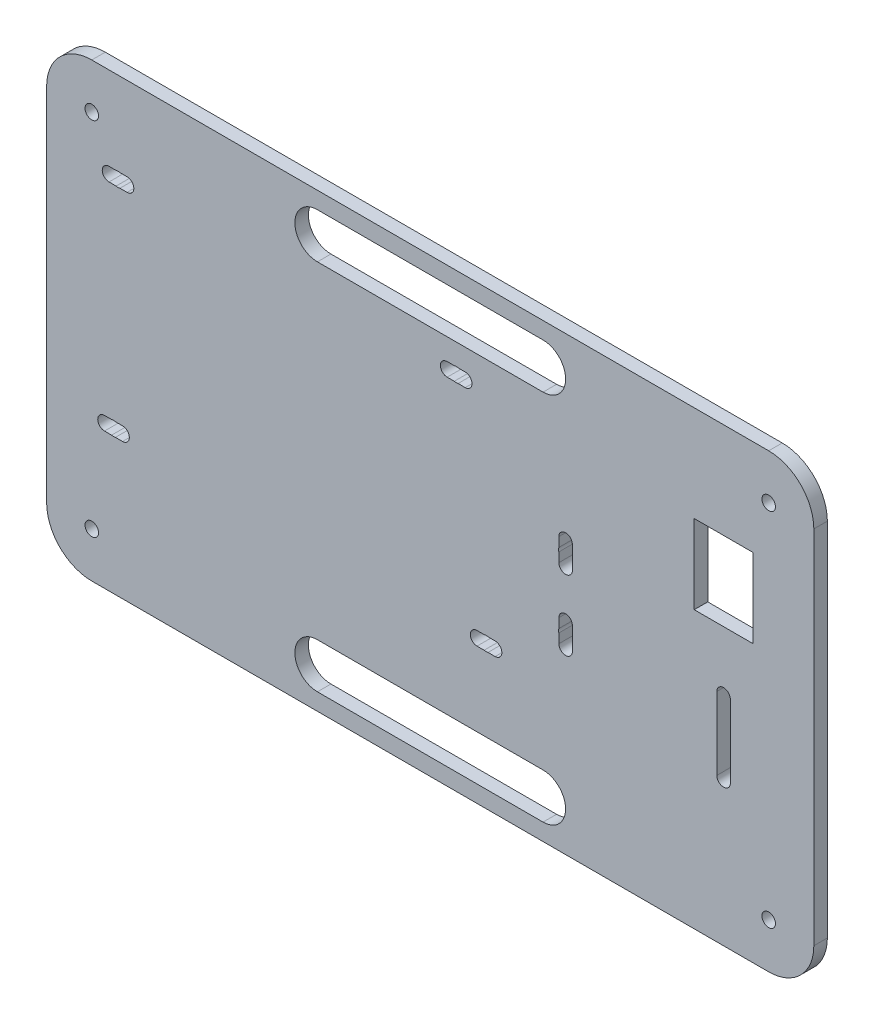
SolidWorks part; units mm, degrees
ref_plane "Front Plane" through (0, 0, 0) normal (0, 0, 1) x (1, 0, 0)
ref_plane "Top Plane" through (0, 0, 0) normal (0, 1, 0) x (1, 0, 0)
ref_plane "Right Plane" through (0, 0, 0) normal (1, 0, 0) x (0, 0, -1)
sketch "Sketch1" plane through (0, 0, 0) normal (0, 0, 1) x (1, 0, 0)
  line L0 (-85, 0) -> (85, 0) construction
  line L1 (-75, 50) -> (75, 50)
  line L2 (-85, 40) -> (-85, -40)
  line L3 (-75, -50) -> (75, -50)
  line L4 (85, 40) -> (85, -40)
  line L5 (-85, 50) -> (85, -50) construction
  line L6 (-85, -50) -> (85, 50) construction
  line L7 (0, 50) -> (0, -50) construction
  line L8 (-25, 41.2578) -> (25, 41.2578) construction
  line L9 (-25, 46.2578) -> (25, 46.2578)
  line L10 (-25, 36.2578) -> (25, 36.2578)
  line L11 (-25, -41.2578) -> (25, -41.2578) construction
  line L12 (-25, -46.2578) -> (25, -46.2578)
  line L13 (-25, -36.2578) -> (25, -36.2578)
  line L14 (30, 5.28) -> (30, 10.28) construction
  line L17 (28.5, 5.28) -> (28.5, 10.28)
  line L18 (31.5, 5.28) -> (31.5, 10.28)
  line L21 (30, -5.28) -> (30, -10.28) construction
  line L24 (28.5, -5.28) -> (28.5, -10.28)
  line L27 (31.5, -5.28) -> (31.5, -10.28)
  line L30 (-67.18, 30) -> (-71.18, 30) construction
  line L31 (-67.18, 28.5) -> (-71.18, 28.5)
  line L34 (-67.18, 31.5) -> (-71.18, 31.5)
  line L39 (65, -1.95) -> (65, -18.05) construction
  line L40 (58.5, 28.75) -> (71.5, 28.75)
  line L41 (58.5, 28.75) -> (58.5, 11.25)
  line L42 (58.5, 11.25) -> (71.5, 11.25)
  line L43 (71.5, 28.75) -> (71.5, 11.25)
  line L44 (58.5, 28.75) -> (71.5, 11.25) construction
  line L45 (58.5, 11.25) -> (71.5, 28.75) construction
  line L46 (66.5, -1.95) -> (66.5, -18.05)
  line L47 (63.5, -1.95) -> (63.5, -18.05)
  line L48 (3.75, 30) -> (7.75, 30) construction
  line L49 (3.75, 31.5) -> (7.75, 31.5)
  line L50 (3.75, 28.5) -> (7.75, 28.5)
  line L51 (10.37, -18.3) -> (14.37, -18.3) construction
  line L52 (10.37, -16.8) -> (14.37, -16.8)
  line L53 (10.37, -19.8) -> (14.37, -19.8)
  line L54 (-72.18, -18.3) -> (-68.18, -18.3) construction
  line L55 (-72.18, -16.8) -> (-68.18, -16.8)
  line L56 (-72.18, -19.8) -> (-68.18, -19.8)
  arc A0 (-25, 46.2578) -> (-25, 36.2578) centre (-25, 41.2578) ccw
  arc A1 (25, 36.2578) -> (25, 46.2578) centre (25, 41.2578) ccw
  arc A2 (-25, -46.2578) -> (-25, -36.2578) centre (-25, -41.2578) cw
  arc A3 (25, -36.2578) -> (25, -46.2578) centre (25, -41.2578) cw
  arc A18 (66.5, -1.95) -> (63.5, -1.95) centre (65, -1.95) ccw
  arc A19 (63.5, -18.05) -> (66.5, -18.05) centre (65, -18.05) ccw
  arc A20 (75, 50) -> (85, 40) centre (75, 40) cw
  arc A21 (85, -40) -> (75, -50) centre (75, -40) cw
  arc A22 (-75, -50) -> (-85, -40) centre (-75, -40) cw
  arc A23 (-75, 50) -> (-85, 40) centre (-75, 40) ccw
  circle A24 centre (-75, 40) radius 1.5
  circle A25 centre (-75, -40) radius 1.5
  circle A26 centre (75, -40) radius 1.5
  circle A27 centre (75, 40) radius 1.5
  circle A30 centre (-69.18, 30) radius 1.56
  circle A31 centre (5.75, 30) radius 1.56
  circle A32 centre (12.37, -18.3) radius 1.56
  circle A33 centre (-70.18, -18.3) radius 1.56
  circle A34 centre (30, 7.78) radius 1.56
  circle A35 centre (30, -7.78) radius 1.56
  arc A36 (28.5, 5.28) -> (31.5, 5.28) centre (30, 5.28) ccw
  arc A37 (31.5, 10.28) -> (28.5, 10.28) centre (30, 10.28) ccw
  arc A38 (28.5, -5.28) -> (31.5, -5.28) centre (30, -5.28) cw
  arc A39 (31.5, -10.28) -> (28.5, -10.28) centre (30, -10.28) cw
  arc A40 (-67.18, 28.5) -> (-67.18, 31.5) centre (-67.18, 30) ccw
  arc A41 (-71.18, 31.5) -> (-71.18, 28.5) centre (-71.18, 30) ccw
  arc A42 (3.75, 31.5) -> (3.75, 28.5) centre (3.75, 30) ccw
  arc A43 (7.75, 28.5) -> (7.75, 31.5) centre (7.75, 30) ccw
  arc A44 (10.37, -16.8) -> (10.37, -19.8) centre (10.37, -18.3) ccw
  arc A45 (14.37, -19.8) -> (14.37, -16.8) centre (14.37, -18.3) ccw
  arc A46 (-72.18, -16.8) -> (-72.18, -19.8) centre (-72.18, -18.3) ccw
  arc A47 (-68.18, -19.8) -> (-68.18, -16.8) centre (-68.18, -18.3) ccw
  point P0 (0, 0)
  point P12 (0, 41.2578)
  point P19 (0, -41.2578)
  point P38 (30, 7.78)
  point P46 (30, -7.78)
  point P51 (-69.18, 30)
  point P58 (5.75, 30)
  point P65 (12.37, -18.3)
  point P72 (-70.18, -18.3)
  point P73 (65, 20)
  point P80 (65, -10)
  dimension "D3" = 5
  dimension "D11" = 74.93
  dimension "D14" = 15.82
  dimension "D17" = 3.12
  dimension "D18" = 30
  dimension "D21" = 1.5
  dimension "D16" = 15.56
  dimension "D28" = 16.1
  dimension "D31" = 10
  dimension "D32" = 3
  dimension "D6" = 3.12
  dimension "D7" = 3.12
  dimension "D8" = 3.12
  dimension "D9" = 3.12
  dimension "D22" = 1.5
  dimension "D1" = 170
  dimension "D2" = 100
  dimension "D4" = 50
  dimension "D5" = 41.2578
  dimension "D10" = 82.55
  dimension "D12" = 48.3
  dimension "D13" = 20
  dimension "D15" = 14.82
  dimension "D19" = 7.78
  dimension "D20" = 5
  dimension "D23" = 4
  dimension "D24" = 13
  dimension "D25" = 17.5
  dimension "D26" = 20
  dimension "D27" = 20
  dimension "D29" = 3
  dimension "D30" = 10
  dimension "D33" = 80
  dimension "D34" = 40
  dimension "D35" = 150
  dimension "D36" = 150
  dimension "D37" = 75
extrude "Boss-Extrude1" add sketch "Sketch1" along normal blind 3 contours L1 A23 L2 A22 L3 A21 L4 A20 A37 L18 A34 A36 L17 A33 A32 A31 A30 A27 A26 A25 A24 L13 A3 L12 A2 L40 L43 L42 L41 A1 L10 A0 L9 A19 L47
